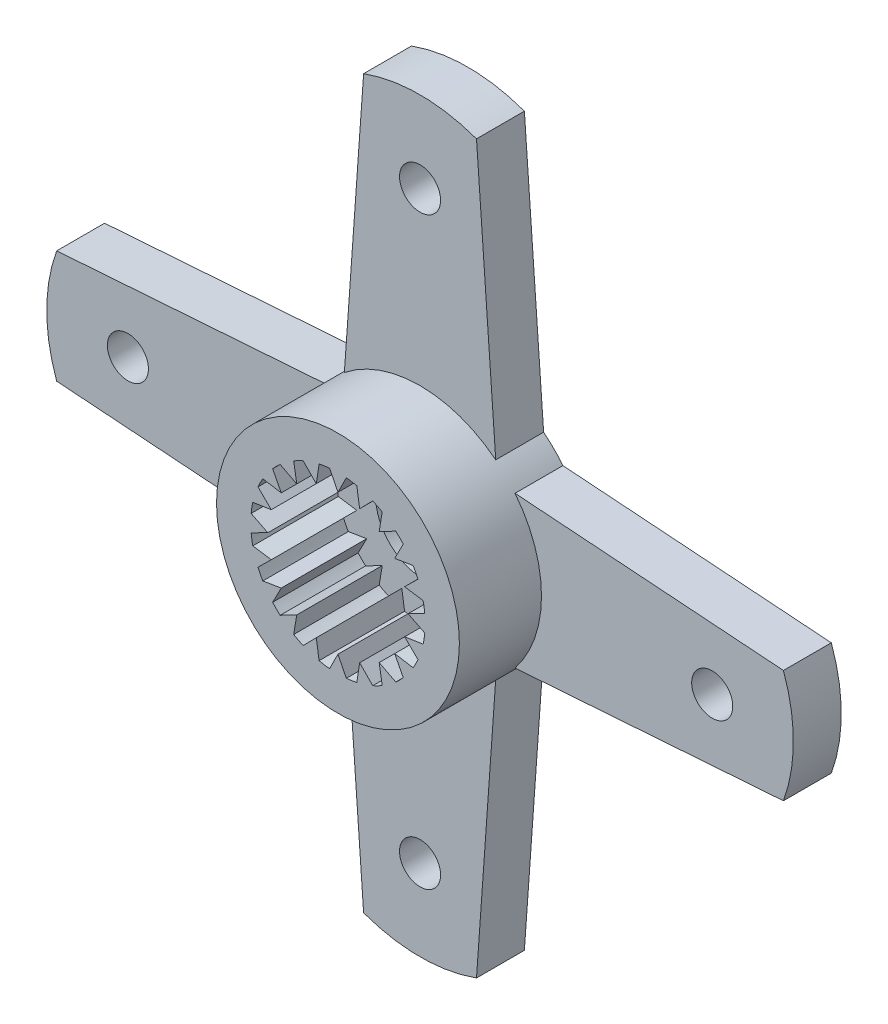
SolidWorks part; units mm, degrees
ref_plane "Front Plane" through (0, 0, 0) normal (0, 0, 1) x (1, 0, 0)
ref_plane "Top Plane" through (0, 0, 0) normal (0, 1, 0) x (1, 0, 0)
ref_plane "Right Plane" through (0, 0, 0) normal (1, 0, 0) x (0, 0, -1)
sketch "Sketch2" plane through (0, 0, 0) normal (0, 0, 1) x (1, 0, 0)
  circle A0 centre (0, 0) radius 3.55
  dimension "D1" = 7.1
sketch "Sketch3" plane through (0, 0, 0) normal (0, 0, 1) x (1, 0, 0)
  line L0 (-0.2447, 2.5382) -> (0, 2.05)
  line L1 (0, 2.05) -> (0.2447, 2.5382)
  line L2 (0.5516, 2.4896) -> (0.6335, 1.9497)
  line L3 (0.6335, 1.9497) -> (1.0171, 2.3384)
  line L4 (1.294, 2.1973) -> (1.205, 1.6585)
  line L5 (1.205, 1.6585) -> (1.6899, 1.9096)
  line L6 (1.9096, 1.6899) -> (1.6585, 1.205)
  line L7 (1.6585, 1.205) -> (2.1973, 1.294)
  line L8 (2.3384, 1.0171) -> (1.9497, 0.6335)
  line L9 (1.9497, 0.6335) -> (2.4896, 0.5516)
  line L10 (2.5382, 0.2447) -> (2.05, 0)
  line L11 (2.05, 0) -> (2.5382, -0.2447)
  line L12 (2.4896, -0.5516) -> (1.9497, -0.6335)
  line L13 (1.9497, -0.6335) -> (2.3384, -1.0171)
  line L14 (2.1973, -1.294) -> (1.6585, -1.205)
  line L15 (1.6585, -1.205) -> (1.9096, -1.6899)
  line L16 (1.6899, -1.9096) -> (1.205, -1.6585)
  line L17 (1.205, -1.6585) -> (1.294, -2.1973)
  line L18 (1.0171, -2.3384) -> (0.6335, -1.9497)
  line L19 (0.6335, -1.9497) -> (0.5516, -2.4896)
  line L20 (0.2447, -2.5382) -> (0, -2.05)
  line L21 (0, -2.05) -> (-0.2447, -2.5382)
  line L22 (-0.5516, -2.4896) -> (-0.6335, -1.9497)
  line L23 (-0.6335, -1.9497) -> (-1.0171, -2.3384)
  line L24 (-1.294, -2.1973) -> (-1.205, -1.6585)
  line L25 (-1.205, -1.6585) -> (-1.6899, -1.9096)
  line L26 (-1.9096, -1.6899) -> (-1.6585, -1.205)
  line L27 (-1.6585, -1.205) -> (-2.1973, -1.294)
  line L28 (-2.3384, -1.0171) -> (-1.9497, -0.6335)
  line L29 (-1.9497, -0.6335) -> (-2.4896, -0.5516)
  line L30 (-2.5382, -0.2447) -> (-2.05, 0)
  line L31 (-2.05, 0) -> (-2.5382, 0.2447)
  line L32 (-2.4896, 0.5516) -> (-1.9497, 0.6335)
  line L33 (-1.9497, 0.6335) -> (-2.3384, 1.0171)
  line L34 (-2.1973, 1.294) -> (-1.6585, 1.205)
  line L35 (-1.6585, 1.205) -> (-1.9096, 1.6899)
  line L36 (-1.6899, 1.9096) -> (-1.205, 1.6585)
  line L37 (-1.205, 1.6585) -> (-1.294, 2.1973)
  line L38 (-1.0171, 2.3384) -> (-0.6335, 1.9497)
  line L39 (-0.6335, 1.9497) -> (-0.5516, 2.4896)
  arc A0 (-0.2447, 2.5382) -> (0.2447, 2.5382) centre (0, 0) cw
  arc A2 (0.5516, 2.4896) -> (1.0171, 2.3384) centre (0, 0) cw
  arc A3 (1.294, 2.1973) -> (1.6899, 1.9096) centre (0, 0) cw
  arc A4 (1.9096, 1.6899) -> (2.1973, 1.294) centre (0, 0) cw
  arc A5 (2.3384, 1.0171) -> (2.4896, 0.5516) centre (0, 0) cw
  arc A6 (2.5382, 0.2447) -> (2.5382, -0.2447) centre (0, 0) cw
  arc A7 (2.4896, -0.5516) -> (2.3384, -1.0171) centre (0, 0) cw
  arc A8 (2.1973, -1.294) -> (1.9096, -1.6899) centre (0, 0) cw
  arc A9 (1.6899, -1.9096) -> (1.294, -2.1973) centre (0, 0) cw
  arc A10 (1.0171, -2.3384) -> (0.5516, -2.4896) centre (0, 0) cw
  arc A11 (0.2447, -2.5382) -> (-0.2447, -2.5382) centre (0, 0) cw
  arc A12 (-0.5516, -2.4896) -> (-1.0171, -2.3384) centre (0, 0) cw
  arc A13 (-1.294, -2.1973) -> (-1.6899, -1.9096) centre (0, 0) cw
  arc A14 (-1.9096, -1.6899) -> (-2.1973, -1.294) centre (0, 0) cw
  arc A15 (-2.3384, -1.0171) -> (-2.4896, -0.5516) centre (0, 0) cw
  arc A16 (-2.5382, -0.2447) -> (-2.5382, 0.2447) centre (0, 0) cw
  arc A17 (-2.4896, 0.5516) -> (-2.3384, 1.0171) centre (0, 0) cw
  arc A18 (-2.1973, 1.294) -> (-1.9096, 1.6899) centre (0, 0) cw
  arc A19 (-1.6899, 1.9096) -> (-1.294, 2.1973) centre (0, 0) cw
  arc A20 (-1.0171, 2.3384) -> (-0.5516, 2.4896) centre (0, 0) cw
  point P66 (0, 0)
  dimension "D1" = 20
ref_plane "Plane1" through (0, 0, -2.4) normal (0, 0, 1) x (1, 0, 0)
sketch "Sketch4" plane through (0, 0, -2.4) normal (0, 0, 1) x (1, 0, 0)
  line L0 (2.7764, 2.2123) -> (10.6226, 1.65)
  line L1 (2.7764, -2.2123) -> (10.6226, -1.65)
  arc A0 (10.6226, 1.65) -> (10.6226, -1.65) centre (6.0891, 0) cw
  arc A1 (2.7764, 2.2123) -> (2.7764, -2.2123) centre (0, 0) cw
extrude "Boss-Extrude1" add sketch "Sketch2" against normal blind 3.8 contours A0
extrude "Boss-Extrude2" add sketch "Sketch4" against normal blind 1.4
sketch "Sketch5" plane through (0, 0, 0) normal (0, 0, 1) x (1, 0, 0)
  circle A0 centre (0, 0) radius 2.55
extrude "Cut-Extrude1" cut sketch "Sketch5" against normal blind 2.5
extrude "Boss-Extrude3" add sketch "Sketch3" against normal up to surface (2.5 mm away) up to face at (2.55, 0, -2.5)
sketch "Sketch6" plane through (0, 0, -2.5) normal (0, 0, 1) x (1, 0, 0)
  circle A0 centre (0, 0) radius 1.4
  dimension "D1" = 2.8
extrude "Cut-Extrude2" cut sketch "Sketch6" against normal through all
sketch "Sketch7" plane through (0, 0, -2.4) normal (0, 0, 1) x (1, 0, 0)
  circle A0 centre (8.5405, 0) radius 0.6
  dimension "D1" = 1.2
extrude "Cut-Extrude3" cut sketch "Sketch7" against normal through all
pattern_circular "CirPattern1" count 4 over 360 about axis through (0, 0, 0) along (0, 0, 1) of "Boss-Extrude2"
pattern_circular "CirPattern2" count 4 over 360 about axis through (0, 0, 0) along (0, 0, 1) of "Cut-Extrude3"
